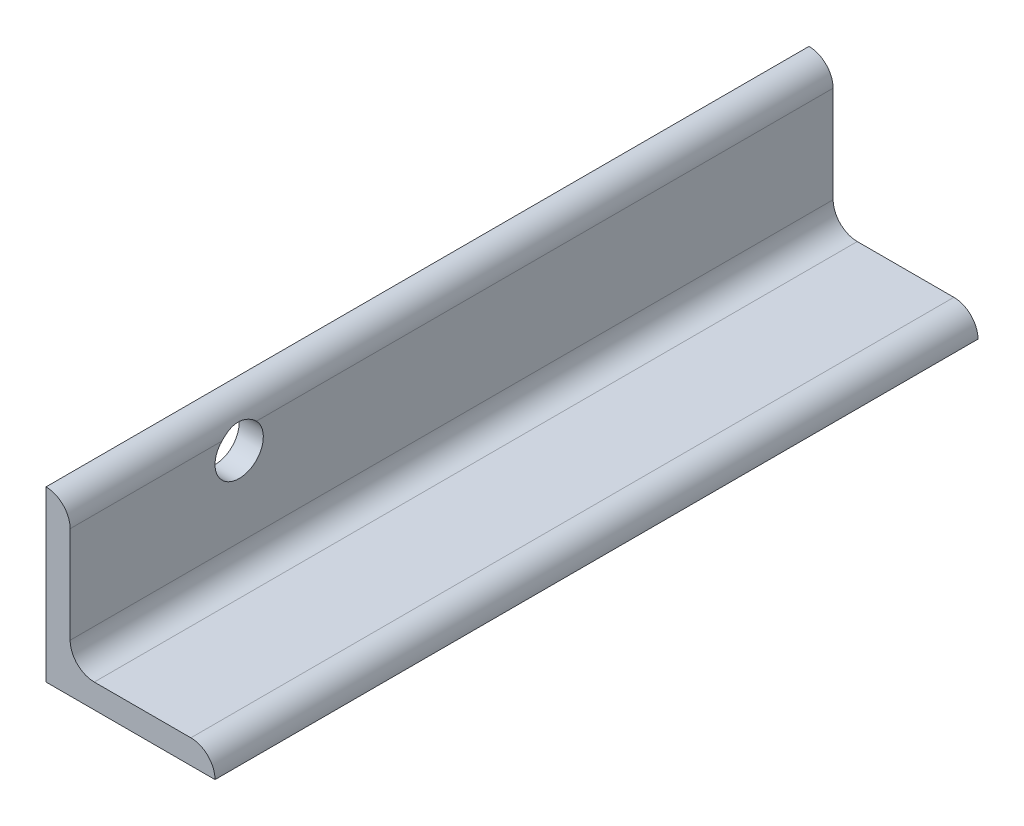
SolidWorks part; units mm, degrees
ref_plane "Płaszczyzna przednia" through (0, 0, 0) normal (0, 0, 1) x (1, 0, 0)
ref_plane "Płaszczyzna górna" through (0, 0, 0) normal (0, 1, 0) x (1, 0, 0)
ref_plane "Płaszczyzna prawa" through (0, 0, 0) normal (1, 0, 0) x (0, 0, -1)
sketch "Szkic1" plane through (0, 0, 0) normal (1, 0, 0) x (0, 0, -1)
  line L0 (-79, 0) -> (79, 0)
  point P3 (0, 0)
  dimension "D1" = 158
other "Kątownik stalowy 35 X 35 X 5(1)"
ref_plane "Płaszczyzna1" through (0, 0, 79) normal (0, 0, -1) x (0, 1, 0)
sketch "Sketch1" plane through (0, 0, 79) normal (0, 0, -1) x (0, 1, 0)
  line L0 (0, 0) -> (0, 35)
  line L1 (0, 17.5) -> (5, 17.5) construction
  line L2 (5, 30) -> (5, 10)
  line L3 (10, 5) -> (30, 5)
  line L4 (17.5, 5) -> (17.5, 0) construction
  line L5 (35, 0) -> (0, 0)
  arc A0 (35, 0) -> (30, 5) centre (30, 0) ccw
  arc A1 (0, 35) -> (5, 30) centre (0, 30) cw
  arc A2 (10, 5) -> (5, 10) centre (10, 10) cw
  point P10 (17.5, 0)
  point P14 (0, 17.5)
  point P15 (5, 17.5)
  point P16 (17.5, 5)
  point P17 (5, 35)
  point P18 (35, 5)
  point P21 (0, 0)
  dimension "D2" = 5
  dimension "D3" = 35
  dimension "Radius_1" = 5
  dimension "D1" = 5
sketch "Szkic3" plane through (0, 0, 0) normal (-1, 0, 0) x (0, 0, 1)
  line L0 (-79, 35) -> (79, 35) construction
  line L1 (79, 0) -> (79, 35) construction
  circle A0 centre (44, 26.5) radius 5
  point P2 (0, 0)
  point P5 (0, 0)
  point P8 (53.7287, 14.8476)
  dimension "D1" = 10
  dimension "D2" = 8.5
  dimension "D3" = 35
extrude "Wytnij-wyciągnięcie1" cut sketch "Szkic3" against normal blind 10
